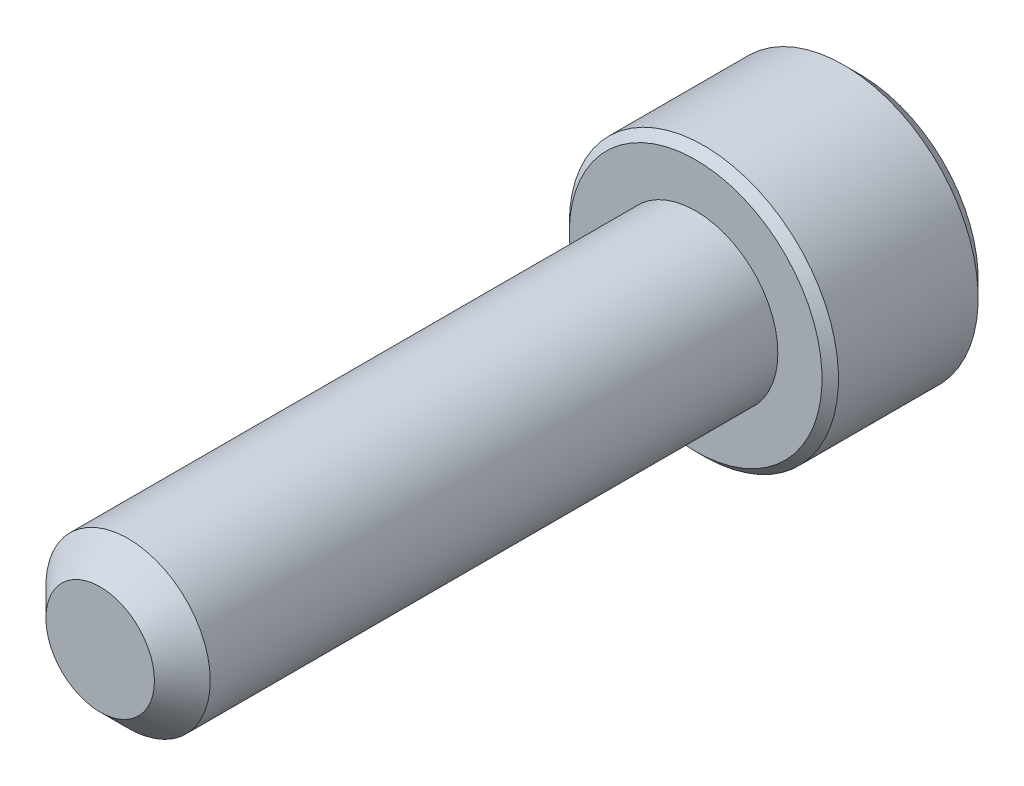
SolidWorks part; units mm, degrees
material "Plain Carbon Steel"
ref_plane "Front Plane" through (0, 0, 0) normal (0, 0, 1) x (1, 0, 0)
ref_plane "Top Plane" through (0, 0, 0) normal (0, 1, 0) x (1, 0, 0)
ref_plane "Right Plane" through (0, 0, 0) normal (1, 0, 0) x (0, 0, -1)
sketch "Sketch1" plane through (0, 0, 0) normal (0, 0, 1) x (1, 0, 0)
  line L0 (0, 1.7526) -> (0, -1.7526) construction
  circle A0 centre (0, 0) radius 1.7526
  dimension "OD" = 3.5052
extrude "Extrude1" add sketch "Sketch1" against normal blind 12.7
sketch "Sketch2" plane through (0, 0, 0) normal (0, 0, 1) x (1, 0, 0)
  circle A0 centre (0, 0) radius 1.7526 construction
  circle A1 centre (0, 0) radius 1.7526
curve "Helix/Spiral1" pitch 0.7937 height 13.4937 turns 17 parameters "pitch"=0.7937
chamfer "Chamfer3" distance 0.5953 angle 45 1 edges at (1.7526, 0, 0)
sketch "Sketch3" plane through (0, 0, 0) normal (1, 0, 0) x (0, 0, -1)
  line L0 (-0.6945, 1.7526) -> (-0.3969, 1.237)
  line L1 (-0.3969, 1.237) -> (-0.2977, 1.237)
  line L2 (-0.2977, 1.237) -> (0, 1.7526)
  line L3 (-0.6945, 1.7526) -> (0, 1.7526)
  line L4 (-0.3473, 1.7526) -> (-0.3473, 1.237) construction
  line L5 (-0.5457, 1.4948) -> (-0.1488, 1.4948) construction
  line L6 (0, 1.7526) -> (0, -1.7526) construction
  dimension "D1" = 0.0992
  dimension "D2" = 0.3969
  dimension "D3" = 60
sketch "Sketch6" plane through (0, 0, -12.7) normal (0, 0, -1) x (-1, 0, 0)
  circle A0 centre (0, 0) radius 2.8702
  dimension "head dia" = 5.7404
extrude "Extrude2" add sketch "Sketch6" along normal blind 3.5052
sketch "Sketch7" plane through (0, 0, -16.2052) normal (0, 0, -1) x (-1, 0, 0)
  line L1 (0, 1.604) -> (-1.3891, 0.802)
  line L2 (-1.3891, 0.802) -> (-1.3891, -0.802)
  line L3 (-1.3891, -0.802) -> (0, -1.604)
  line L4 (0, -1.604) -> (1.3891, -0.802)
  line L5 (1.3891, -0.802) -> (1.3891, 0.802)
  line L6 (1.3891, 0.802) -> (0, 1.604)
  circle A0 centre (0, 0) radius 1.3891 construction
  dimension "hex dia" = 2.7781
extrude "Cut-Extrude1" cut sketch "Sketch7" against normal blind 2.0836
sketch "Sketch8" plane through (0, 0, -16.2052) normal (0, 0, -1) x (-1, 0, 0)
  circle A0 centre (0, 0) radius 1.604
extrude "Cut-Extrude2" cut sketch "Sketch8" against normal blind 0.3505 draft 45
chamfer "Chamfer1" distance 0.3505 angle 45 1 edges at (-2.8702, 0, -16.2052)
chamfer "Chamfer2" distance 0.1753 angle 45 1 edges at (-2.8702, 0, -12.7)
sketch "Sketch9" plane through (0, 0, 0) normal (1, 0, 0) x (0, 0, -1)
  line L0 (0, 1.7526) -> (0, -1.7526) construction
  line L1 (4.3656, 1.7526) -> (4.3656, -1.7526) construction
  line L2 (12.7, 2.8702) -> (12.7, -2.8702) construction
  line L3 (16.2052, 2.8702) -> (16.2052, -2.8702) construction
  line L4 (16.2052, 0) -> (0, 0) construction
  dimension "D1" = 4.3656
  dimension "D2" = 3.5052
  dimension "D3" = 5.7404
  dimension "D4" = 12.7
equation "\"D3@Helix/Spiral1\" = \"screw length@Extrude1\"+\"pitch@Helix/Spiral1\""
equation "\"D1@Sketch3\" = \"pitch@Helix/Spiral1\"*.125"
equation "\"D2@Sketch3\" = \"pitch@Helix/Spiral1\"*.5"
equation "\"D1@Cut-Extrude1\" = \"hex dia@Sketch7\"*.75"
equation "\"D1@Chamfer1\" = \"head depth@Extrude2\"/10"
equation "\"D1@Sketch9\" = \"pitch@Helix/Spiral1\"*5.5"
equation "\"D1@Chamfer2\" = \"D1@Chamfer1\"/2"
equation "\"D1@Cut-Extrude2\" = \"D1@Chamfer2\"*2"
equation "\"D1@Chamfer3\" = \"pitch@Helix/Spiral1\"*.750"
equation "\"D2@Sketch9\" = \"head depth@Extrude2\""
equation "\"D3@Sketch9\" = \"head dia@Sketch6\""
equation "\"D4@Sketch9\" = \"screw length@Extrude1\""
